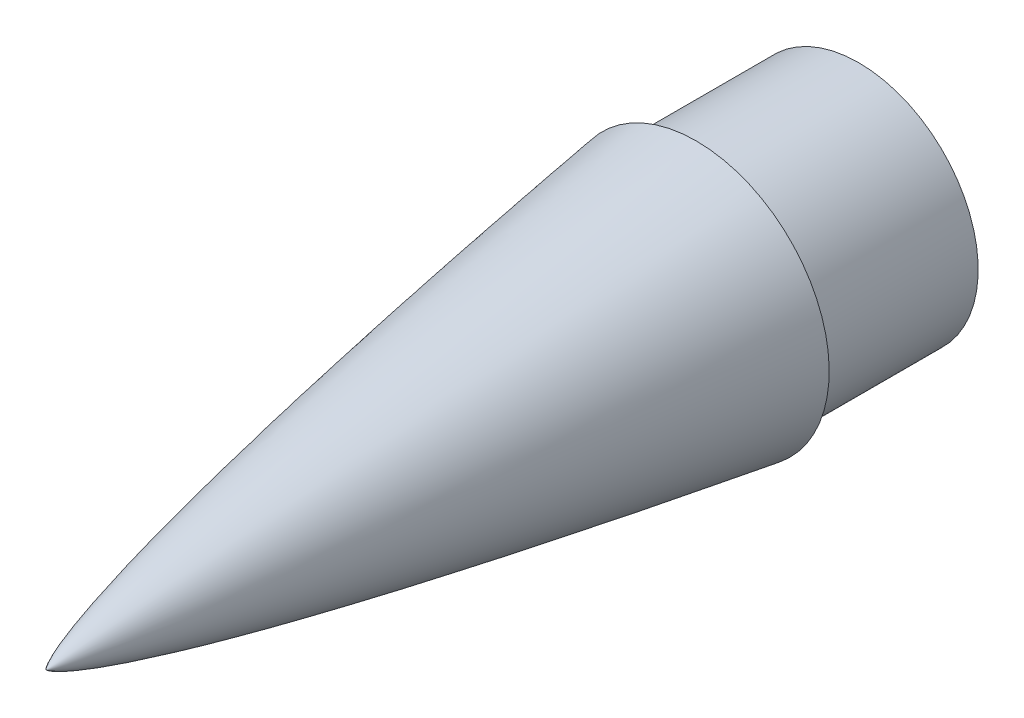
SolidWorks part; units mm, degrees
material "6061 Alloy"
ref_plane "Front Plane" through (0, 0, 0) normal (0, 0, 1) x (1, 0, 0)
ref_plane "Top Plane" through (0, 0, 0) normal (0, 1, 0) x (1, 0, 0)
ref_plane "Right Plane" through (0, 0, 0) normal (1, 0, 0) x (0, 0, -1)
sketch "Sketch1" plane through (0, 0, 0) normal (1, 0, 0) x (0, 0, -1)
  line L0 (76.2, 15.58) -> (76.2, 0)
  line L1 (76.2, 0) -> (0, 0)
  spline S0 degree 4 poles (0, 0) (0.0028, 0.0075) (0.0101, 0.0216) (0.0291, 0.0445) (0.059, 0.0751) (0.0993, 0.1103) (0.1563, 0.1548) (0.2393, 0.2131) (0.372, 0.2968) (0.5902, 0.42) (0.9651, 0.6078) (1.6199, 0.897) (2.7739, 1.3432) (4.7238, 2.0005) (7.8801, 2.9306) (12.1153, 4.0292) (17.1941, 5.2178) (22.7695, 6.4196) (28.3686, 7.551) (33.9649, 8.6242) (39.5923, 9.6549) (45.1892, 10.6415) (50.8558, 11.6042) (55.7152, 12.4057) (60.0474, 13.1007) (63.4013, 13.6316) (66.5237, 14.1155) (69.4663, 14.5711) (74.2527, 15.2917) (77.11, 15.7166) (81.1603, 16.3095) (82.8015, 16.5457) (83.8354, 16.6947) knots 0 0 0 0 0 0.000373 0.000746 0.001374 0.002002 0.002868 0.004119 0.006112 0.009325 0.014564 0.023687 0.039533 0.067072 0.110645 0.177267 0.243888 0.310509 0.37713 0.443752 0.510373 0.576994 0.643616 0.710237 0.743548 0.776858 0.810169 0.84348 0.910101 0.95505 1 1 1 1 1 construction
  spline S1 degree 4 poles (0, 0) (0.0028, 0.0075) (0.0101, 0.0216) (0.0291, 0.0445) (0.059, 0.0751) (0.0993, 0.1103) (0.1563, 0.1548) (0.2393, 0.2131) (0.372, 0.2968) (0.5902, 0.42) (0.9651, 0.6078) (1.6199, 0.897) (2.7739, 1.3432) (4.7238, 2.0005) (7.8801, 2.9306) (12.1153, 4.0292) (17.1941, 5.2178) (22.7695, 6.4196) (28.3686, 7.551) (33.9649, 8.6242) (39.5923, 9.6549) (45.1892, 10.6415) (50.8558, 11.6042) (55.7152, 12.4057) (60.0474, 13.1007) (63.4013, 13.6316) (66.5237, 14.1155) (69.4663, 14.5711) (73.0453, 15.1099) (74.9156, 15.3896) (76.2, 15.58) knots 0 0 0 0 0 0.000373 0.000746 0.001374 0.002002 0.002868 0.004119 0.006112 0.009325 0.014564 0.023687 0.039533 0.067072 0.110645 0.177267 0.243888 0.310509 0.37713 0.443752 0.510373 0.576994 0.643616 0.710237 0.743548 0.776858 0.810169 0.84348 0.910101 0.910101 0.910101 0.910101 0.910101
revolve "Revolve1" add sketch "Sketch1" angle 360 about L1
sketch "Sketch2" plane through (0, 0, -76.2) normal (0, 0, -1) x (-1, 0, 0)
  circle A0 centre (0, 0) radius 13.9925
  circle A1 centre (0, 0) radius 15.58 construction
  dimension "D1" = 1.5875
extrude "Boss-Extrude1" add sketch "Sketch2" along normal blind 19.05
hole_wizard "1/4-20 Tapped Hole1" positions "Sketch5" profile "Sketch3" tap size "1/4-20" standard "ANSI Inch"
sketch "Sketch5" plane through (0, 0, -95.25) normal (0, 0, -1) x (-1, 0, 0)
  point P0 (0, 0)
sketch "Sketch3" plane through (0, 0, -95.25) normal (1, 0, 0) x (0, 1, 0)
  line L0 (0, 0) -> (0, 39.6338)
  line L1 (0, 39.6338) -> (2.5527, 38.1)
  line L2 (2.5527, 38.1) -> (2.5527, 0)
  line L5 (2.5527, 0) -> (0, 0)
  line L10 (0, 39.6338) -> (-2.5527, 38.1) construction
  line L11 (0, -6.35) -> (0, 107.95) construction
  dimension "Tap Drill Dia." = 5.1054
  dimension "Tap Drill Depth" = 38.1
  dimension "Drill Angle" = 118
cosmetic thread "Hole Thread1" parameters "D1"=12.7, "D2"=6.35
